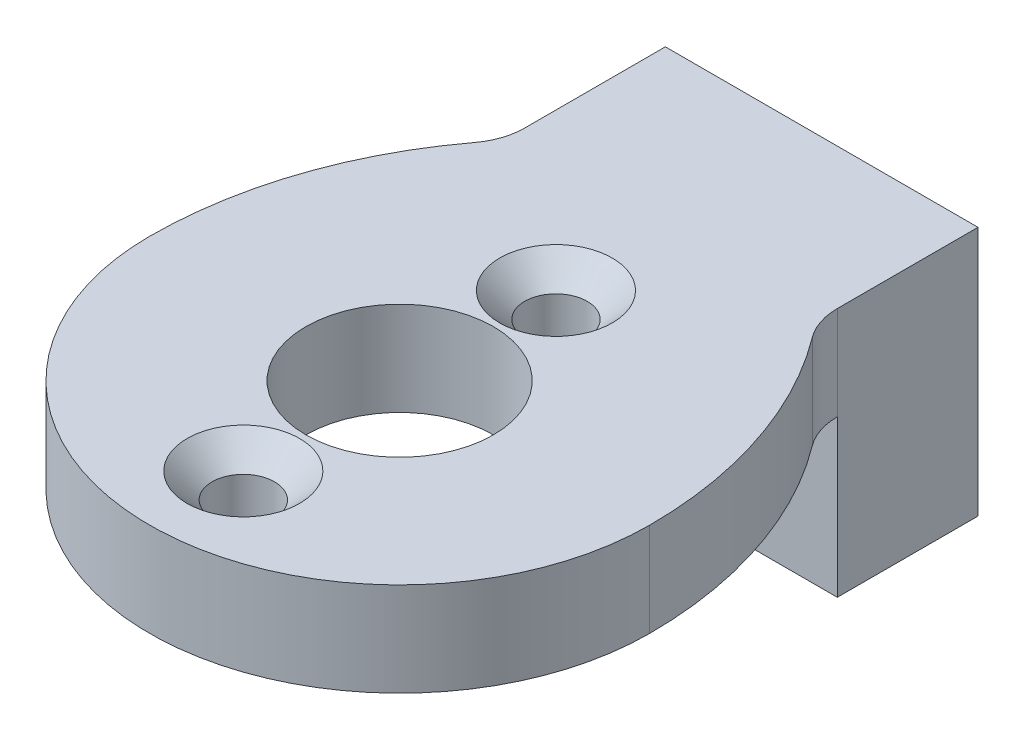
SolidWorks part; units mm, degrees
material "6061 Alloy"
ref_plane "Front Plane" through (0, 0, 0) normal (0, 0, 1) x (1, 0, 0)
ref_plane "Top Plane" through (0, 0, 0) normal (0, 1, 0) x (1, 0, 0)
ref_plane "Right Plane" through (0, 0, 0) normal (1, 0, 0) x (0, 0, -1)
ref_plane "Plane1" through (0, 3, 0) normal (0, 1, 0) x (1, 0, 0)
sketch "Sketch1" plane through (0, 3, 0) normal (0, 1, 0) x (1, 0, 0)
  line L0 (5, -5.1934) -> (5, 0)
  line L1 (5, 0) -> (-5, 0)
  line L2 (-5, 0) -> (-5, -5.1934)
  arc A0 (-5, -5.1934) -> (-8, -13.5) centre (5, -13.5) ccw
  arc A1 (-8, -13.5) -> (8, -13.5) centre (0, -13.5) ccw
  arc A2 (8, -13.5) -> (5, -5.1934) centre (-5, -13.5) ccw
extrude "Boss-Extrude1" add sketch "Sketch1" against normal blind 3
sketch "Sketch2" plane through (0, 0, 0) normal (0, -1, 0) x (1, 0, 0)
  line L0 (-5, 0) -> (-5, 4.5)
  line L1 (-5, 4.5) -> (5, 4.5)
  line L2 (5, 4.5) -> (5, 0)
  line L3 (5, 0) -> (-5, 0)
extrude "Boss-Extrude2" add sketch "Sketch2" along normal blind 5
hole_wizard "Ø6.0 (6) Diameter Hole1" positions "Sketch7" profile "Sketch6" hole size "Ø6.0" standard "ANSI Metric" end condition through all
sketch "Sketch7" plane through (0, 0, 0) normal (0, -1, 0) x (-1, 0, 0)
  point P0 (0, -13.5)
sketch "Sketch6" plane through (0, 0, 13.5) normal (1, 0, 0) x (0, 0, -1)
  line L0 (0, 0) -> (0, 3)
  line L1 (0, 3) -> (3, 3)
  line L2 (3, 3) -> (3, 0)
  line L5 (3, 0) -> (0, 0)
  line L11 (0, -6.35) -> (0, 107.95) construction
  dimension "Thru Hole Dia." = 6
  dimension "Thru Hole Depth" = 3
hole_wizard "M3x0.5 Tapped Hole1" positions "Sketch11" profile "Sketch10" tap size "M3x0.5" standard "ANSI Metric" end condition up to next
sketch "Sketch11" plane through (0, 0, 0) normal (0, 0, -1) x (-1, 0, 0)
  point P0 (-1.5, -2)
sketch "Sketch10" plane through (1.5, -2, 0) normal (1, 0, 0) x (0, 1, 0)
  line L0 (0, 0) -> (0, 4.5)
  line L1 (0, 4.5) -> (1.25, 4.5)
  line L2 (1.25, 4.5) -> (1.25, 0)
  line L5 (1.25, 0) -> (0, 0)
  line L11 (0, -6.35) -> (0, 107.95) construction
  dimension "Thread Major Dia." = 2.5
  dimension "Thru Tap Drill Depth" = 4.5
hole_wizard "M2x0.4 Tapped Hole1" positions "Sketch13" profile "Sketch12" tap size "M2x0.4" standard "ANSI Metric"
sketch "Sketch13" plane through (0, 0, 0) normal (0, 0, -1) x (-1, 0, 0)
  point P0 (3, 1)
sketch "Sketch12" plane through (-3, 1, 0) normal (1, 0, 0) x (0, 1, 0)
  line L0 (0, 0) -> (0, 5.6807)
  line L1 (0, 5.6807) -> (0.8, 5.2)
  line L2 (0.8, 5.2) -> (0.8, 0)
  line L5 (0.8, 0) -> (0, 0)
  line L10 (0, 5.6807) -> (-0.8, 5.2) construction
  line L11 (0, -6.35) -> (0, 107.95) construction
  dimension "Tap Drill Dia." = 1.6
  dimension "Tap Drill Depth" = 5.2
  dimension "Drill Angle" = 118
fillet "Fillet1" radius 2 2 edges at (5, 1.5, 5.1934) (-5, 1.5, 5.1934)
sketch "Sketch15" plane through (0, 3, 0) normal (0, 1, 0) x (1, 0, 0)
  point P0 (0, -8.5)
  point P1 (0, -18.5)
  dimension "D1" = 5
  dimension "D2" = 5
hole_wizard "CSK for M3 SFHCS3" positions "3DSketch2" profile "Sketch16" countersink size "M3" standard "ANSI Metric"
sketch3d "3DSketch2"
  point P0 (0, 3, 8.5)
  point P3 (0, 3, 18.5)
sketch "Sketch16" plane through (0, 3, 8.5) normal (1, 0, 0) x (0, 0, 1)
  line L0 (0, 0) -> (0, 10.1009)
  line L1 (0, 10.1009) -> (1, 9.5)
  line L2 (1, 9.5) -> (1, 0.8)
  line L3 (1, 0.8) -> (1.8, 0)
  line L5 (1.8, 0) -> (0, 0)
  line L6 (-1, 0.8) -> (-1.8, 0) construction
  line L10 (0, 10.1009) -> (-1, 9.5) construction
  line L11 (0, -6.35) -> (0, 107.95) construction
  dimension "Hole Dia." = 2
  dimension "Hole Depth" = 9.5
  dimension "Near C'Sink Dia." = 3.6
  dimension "Near C'Sink Angle" = 90
  dimension "Drill Angle" = 118
